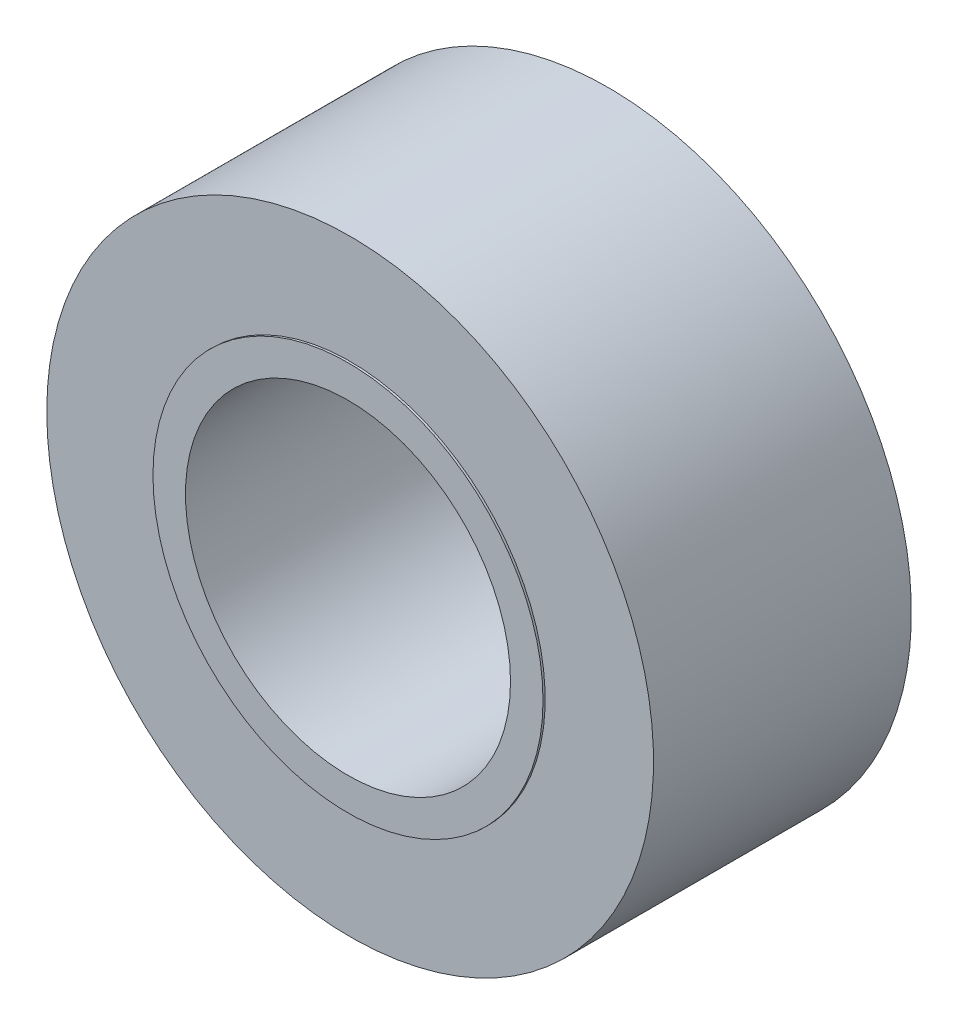
SolidWorks part; units mm, degrees
ref_plane "Alzado" through (0, 0, 0) normal (0, 0, 1) x (1, 0, 0)
ref_plane "Planta" through (0, 0, 0) normal (0, 1, 0) x (1, 0, 0)
ref_plane "Vista lateral" through (0, 0, 0) normal (1, 0, 0) x (0, 0, -1)
sketch "Croquis1" plane through (0, 0, 0) normal (0, 0, 1) x (1, 0, 0)
  circle A0 centre (0, 0) radius 7.5
  circle A1 centre (0, 0) radius 9
  circle A3 centre (0, 0) radius 9
  circle A4 centre (0, 0) radius 1.5
  circle A5 centre (0, 0) radius 7.4545
  circle A6 centre (0, 0) radius 7.5
  dimension "D1" = 15
  dimension "D2" = 18
  dimension "D3" = 3
extrude "Saliente-Extruir1" add sketch "Croquis1" along normal blind 12 contours A1 A0
sketch "Croquis2" plane through (0, 0, 0) normal (0, 0, 1) x (1, 0, 0)
  circle A0 centre (0, 0) radius 7.5
extrude "Saliente-Extruir2" add sketch "Croquis2" along normal blind 1 and the other way blind 0.1
sketch "Croquis3" plane through (0, 0, 0) normal (0, 0, 1) x (1, 0, 0)
  circle A0 centre (0, 0) radius 5.2
  circle A1 centre (0, 0) radius 1.5
  dimension "D1" = 10.4
  dimension "D2" = 3
extrude "Saliente-Extruir4" add sketch "Croquis3" against normal blind 3 contours A0 | A1
sketch "Croquis4" plane through (0, 0, 0) normal (0, 0, -1) x (-1, 0, 0)
  circle A0 centre (0, 0) radius 9
  circle A1 centre (0, 0) radius 14
  dimension "D1" = 28
extrude "Saliente-Extruir5" add sketch "Croquis4" against normal blind 11.9
sketch "Croquis6" plane through (0, 0, -3) normal (0, 0, -1) x (-1, 0, 0)
  circle A0 centre (0, 0) radius 1.5
extrude "Cortar-Extruir1" cut sketch "Croquis6" against normal blind 15
